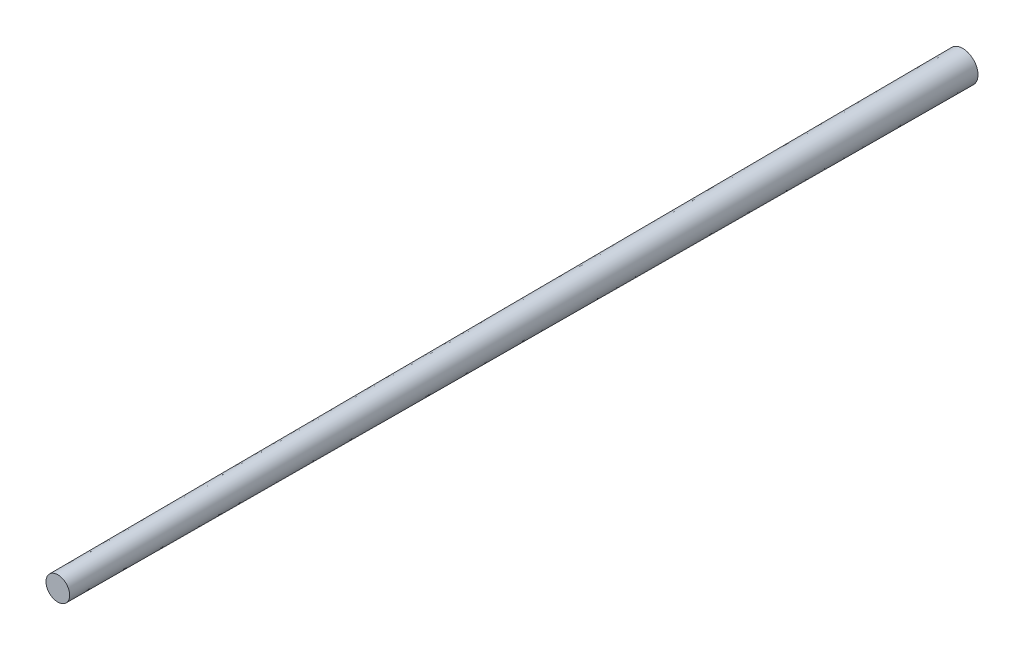
SolidWorks part; units mm, degrees
ref_plane "Front Plane" through (0, 0, 0) normal (0, 0, 1) x (1, 0, 0)
ref_plane "Top Plane" through (0, 0, 0) normal (0, 1, 0) x (1, 0, 0)
ref_plane "Right Plane" through (0, 0, 0) normal (1, 0, 0) x (0, 0, -1)
sketch "Sketch1" plane through (0, 0, 0) normal (0, 0, 1) x (1, 0, 0)
  circle A0 centre (0, 0) radius 22
extrude "NeckPole" add sketch "Sketch1" along normal blind 1300 draft 0.22
